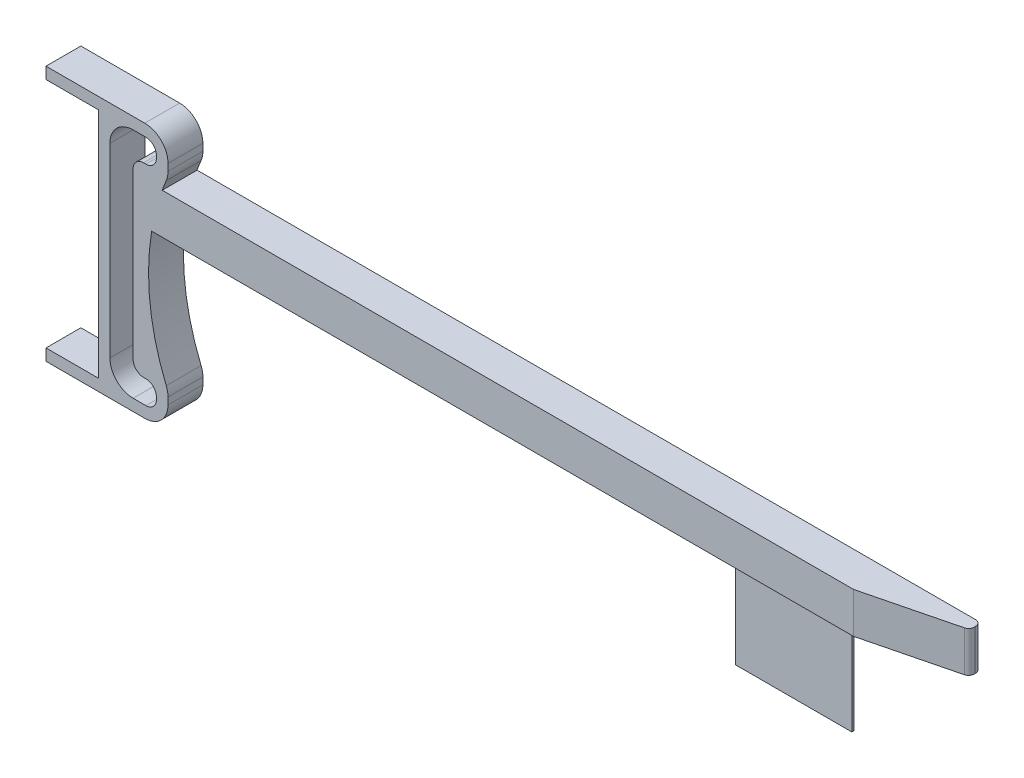
SolidWorks part; units mm, degrees
ref_plane "Front Plane" through (0, 0, 0) normal (0, 0, 1) x (1, 0, 0)
ref_plane "Top Plane" through (0, 0, 0) normal (0, 1, 0) x (1, 0, 0)
ref_plane "Right Plane" through (0, 0, 0) normal (1, 0, 0) x (0, 0, -1)
sketch "Sketch1" plane through (0, 0, 0) normal (0, 0, 1) x (1, 0, 0)
  line L0 (2, 8.9) -> (2, 9.1)
  line L1 (1, -11) -> (-3, -11)
  line L2 (3, -9) -> (3, -8.4086)
  line L3 (-3, -10) -> (-3, 10)
  line L4 (-3, 11) -> (1, 11)
  line L5 (3, -11) -> (-3, 11) construction
  line L6 (3, 11) -> (-3, -11) construction
  line L7 (0, -10) -> (1.1, -10)
  line L8 (-2, -8) -> (-2, 8)
  line L9 (0, 10) -> (1.1, 10)
  line L10 (2, -9.1) -> (2, -8.9)
  line L11 (3, 8.4086) -> (3, 9)
  line L13 (1.1, 8) -> (0.9, 8)
  line L14 (-3, 10) -> (-7.5, 10)
  line L15 (1.1, -8) -> (0.9, -8)
  line L16 (0, 7.1) -> (0, -7.1)
  line L17 (-3, -11) -> (-7.5, -11)
  line L18 (-3, 11) -> (-7.5, 11)
  line L19 (-7.5, 10) -> (-7.5, 11)
  line L21 (-3, -10) -> (-7.5, -10)
  line L22 (-7.5, -11) -> (-7.5, -10)
  arc A0 (0, -10) -> (-2, -8) centre (0, -8) cw
  arc A1 (0, 10) -> (-2, 8) centre (0, 8) ccw
  arc A2 (2, 9.1) -> (1.1, 10) centre (1.1, 9.1) ccw
  arc A3 (2, 8.9) -> (1.1, 8) centre (1.1, 8.9) cw
  arc A4 (2, -9.1) -> (1.1, -10) centre (1.1, -9.1) cw
  arc A5 (2, -8.9) -> (1.1, -8) centre (1.1, -8.9) ccw
  arc A6 (0.9, 8) -> (0, 7.1) centre (0.9, 7.1) ccw
  arc A7 (0.9, -8) -> (0, -7.1) centre (0.9, -7.1) cw
  arc A8 (3, -9) -> (1, -11) centre (1, -9) cw
  arc A10 (3, 9) -> (1, 11) centre (1, 9) ccw
  arc A12 (2.8471, 7.6417) -> (2.8471, -7.6417) centre (21.2517, 0) ccw
  arc A13 (3, -8.4086) -> (2.8471, -7.6417) centre (1, -8.4086) ccw
  arc A14 (3, 8.4086) -> (2.8471, 7.6417) centre (1, 8.4086) cw
  point P0 (0, 0)
  point P6 (0, 0)
  point P18 (2, 10)
  point P24 (2, 8)
  point P27 (2, -10)
  point P53 (3, 8)
  point P60 (-8, 10)
  point P63 (-8, -10)
  dimension "D5" = 2
  dimension "D7" = 0.9
  dimension "D8" = 0.9
  dimension "D9" = 0.9
  dimension "D10" = 2
  dimension "D11" = 2
  dimension "D1" = 22
  dimension "D2" = 6
  dimension "D3" = 2
  dimension "D4" = 20
  dimension "D6" = 2
  dimension "D12" = 4.5
  dimension "D13" = 1
  dimension "D14" = 4.5
extrude "Hook" add sketch "Sketch1" along normal blind 3
sketch "Sketch2" plane through (0, 0, 0) normal (0, 0, 1) x (1, 0, 0)
  line L0 (0, 5) -> (70, 5) construction
  line L1 (0, 6.75) -> (70, 6.75)
  line L2 (0, 6.75) -> (0, 3.25)
  line L3 (0, 3.25) -> (70, 3.25)
  line L4 (70, 6.75) -> (70, 3.25)
  dimension "D1" = 3.5
  dimension "D2" = 5
  dimension "D3" = 70
extrude "Pin" add sketch "Sketch2" along normal up to surface (3 mm away) up to face at (-1.2089, 0, 3)
sketch "Sketch3" plane through (0, 3.25, 0) normal (0, -1, 0) x (1, 0, 0)
  line L0 (62, 3) -> (70, 3)
  line L1 (70, 3) -> (1.5905, 3) construction
  line L2 (70, 3) -> (70, 1)
  line L3 (70, 3) -> (70, 0) construction
  line L4 (70, 1) -> (62, 3)
  dimension "D1" = 1
  dimension "D2" = 8
extrude "Cut-Extrude1" cut sketch "Sketch3" against normal up to surface (3.5 mm away) up to face at (36.2509, 6.75, 1.5)
fillet "Fillet1" radius 0.5 2 edges at (70, 5, 0) (70, 5, 1)
sketch "Sketch4" plane through (0, 0, 0) normal (0, 0, 1) x (1, 0, 0)
  line L0 (62, 3.25) -> (1.5905, 3.25) construction
  line L1 (49.0478, 3.25) -> (59.0478, 3.25)
  line L2 (49.0478, 3.25) -> (49.0478, -6.75)
  line L3 (49.0478, -6.75) -> (59.0478, -6.75)
  line L4 (59.0478, 3.25) -> (59.0478, -6.75)
  dimension "D1" = 10
  dimension "D2" = 10
extrude "Boss-Extrude3" add sketch "Sketch4" along normal blind 0.2
